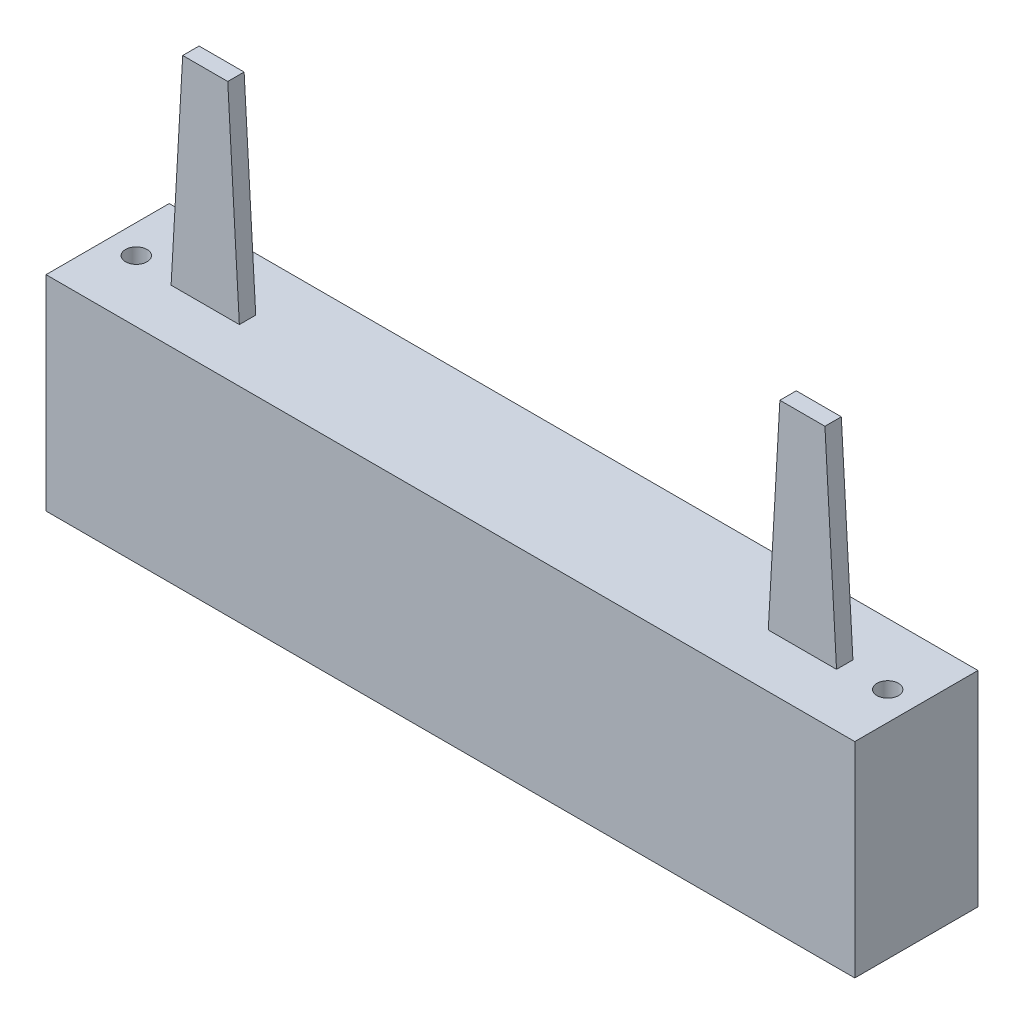
SolidWorks part; units mm, degrees
material "Copper"
ref_plane "Front Plane" through (0, 0, 0) normal (0, 0, 1) x (1, 0, 0)
ref_plane "Top Plane" through (0, 0, 0) normal (0, 1, 0) x (1, 0, 0)
ref_plane "Right Plane" through (0, 0, 0) normal (1, 0, 0) x (0, 0, -1)
sketch "Sketch1" plane through (0, 0, 0) normal (0, 1, 0) x (1, 0, 0)
  line L1 (0, 0) -> (60.198, 0)
  line L2 (0, 0) -> (0, 9.1694)
  line L3 (0, 9.1694) -> (60.198, 9.1694)
  line L4 (60.198, 0) -> (60.198, 9.1694)
  dimension "D1" = 60.198
  dimension "D2" = 9.1694
extrude "Boss-Extrude1" add sketch "Sketch1" along normal blind 15.24
sketch "Sketch2" plane through (0, 15.24, 0) normal (0, 1, 0) x (1, 0, 0)
  line L0 (60.198, 0) -> (60.198, 9.1694) construction
  line L1 (5.334, 5.1943) -> (54.864, 5.1943)
  line L2 (5.334, 5.1943) -> (5.334, 3.9751)
  line L3 (5.334, 3.9751) -> (54.864, 3.9751)
  line L4 (54.864, 5.1943) -> (54.864, 3.9751)
  line L5 (0, 9.1694) -> (0, 0) construction
  line L6 (54.864, 4.5847) -> (60.198, 4.5847) construction
  line L7 (49.784, 5.1943) -> (49.784, 3.9751)
  line L8 (10.414, 5.1943) -> (10.414, 3.9751)
  dimension "D1" = 5.334
  dimension "D2" = 5.334
  dimension "D3" = 1.2192
  dimension "D4" = 5.08
  dimension "D5" = 5.08
extrude "Boss-Extrude2" add sketch "Sketch2" along normal blind 15.24 contours L8 L1 L2 L3 | L1 L7 L3 L4
sketch "Sketch3" plane through (0, 0, -3.9751) normal (0, 0, 1) x (1, 0, 0)
  line L0 (6.1976, 30.48) -> (9.5504, 30.48)
  line L1 (5.334, 30.48) -> (10.414, 30.48) construction
  line L2 (6.1976, 30.48) -> (5.334, 15.24)
  line L3 (5.334, 15.24) -> (5.334, 30.48)
  line L4 (5.334, 30.48) -> (6.1976, 30.48)
  line L5 (9.5504, 30.48) -> (10.414, 15.24)
  line L6 (10.414, 15.24) -> (10.414, 30.48)
  line L7 (10.414, 30.48) -> (9.5504, 30.48)
  point P4 (7.874, 30.48)
  point P5 (7.874, 30.48)
  line M3 (10.414, 15.24) -> (10.414, 30.48)
  line M4 (10.414, 30.48) -> (5.334, 30.48)
  line M5 (5.334, 30.48) -> (5.334, 15.24)
  dimension "D1" = 3.3528
extrude "Cut-Extrude1" cut sketch "Sketch3" against normal up to next contours L2 M4 M5 | L5 M4 M3
ref_plane "Plane1" through (30.099, 0, 0) normal (1, 0, 0) x (0, 0, -1)
mirror "Mirror1" about plane through (30.099, 0, 0) normal (1, 0, 0) of "Cut-Extrude1"
sketch "Sketch4" plane through (0, 15.24, 0) normal (0, 1, 0) x (1, 0, 0)
  line L0 (0, 4.5847) -> (2.1336, 4.5847) construction
  line L1 (0, 9.1694) -> (0, 0) construction
  line L2 (2.1336, 4.5847) -> (58.0644, 4.5847) construction
  line L3 (30.099, 4.5847) -> (30.099, 0) construction
  line L5 (0, 0) -> (60.198, 0) construction
  dimension "D1" = 55.9308
hole_wizard "M2x0.4 Tapped Hole1" positions "Sketch5" profile "Sketch6" tap size "M2x0.4" standard "ANSI Metric"
sketch "Sketch5" plane through (0, 15.24, 0) normal (0, 1, 0) x (1, 0, 0)
  point P0 (2.1336, 4.5847)
  point P3 (58.0644, 4.5847)
sketch "Sketch6" plane through (2.1336, 15.24, -4.5847) normal (1, 0, 0) x (0, 0, 1)
  line L0 (0, 0) -> (0, 3.048)
  line L1 (0, 3.048) -> (0.8, 2.5673)
  line L2 (0.8, 2.5673) -> (0.8, 0)
  line L5 (0.8, 0) -> (0, 0)
  line L10 (0, 3.048) -> (-0.8, 2.5673) construction
  line L11 (0, -6.35) -> (0, 107.95) construction
  dimension "Tap Drill Dia." = 1.6
  dimension "Tap Drill Depth" = 3.048
  dimension "Drill Angle" = 118
cosmetic thread "Hole Thread1" parameters "D1"=2.5673, "D2"=2
cosmetic thread "Hole Thread2" parameters "D1"=2.5673, "D2"=2
equation "\"D2@Sketch2\"=\"D1@Sketch2\""
equation "\"D5@Sketch2\"=\"D4@Sketch2\""
